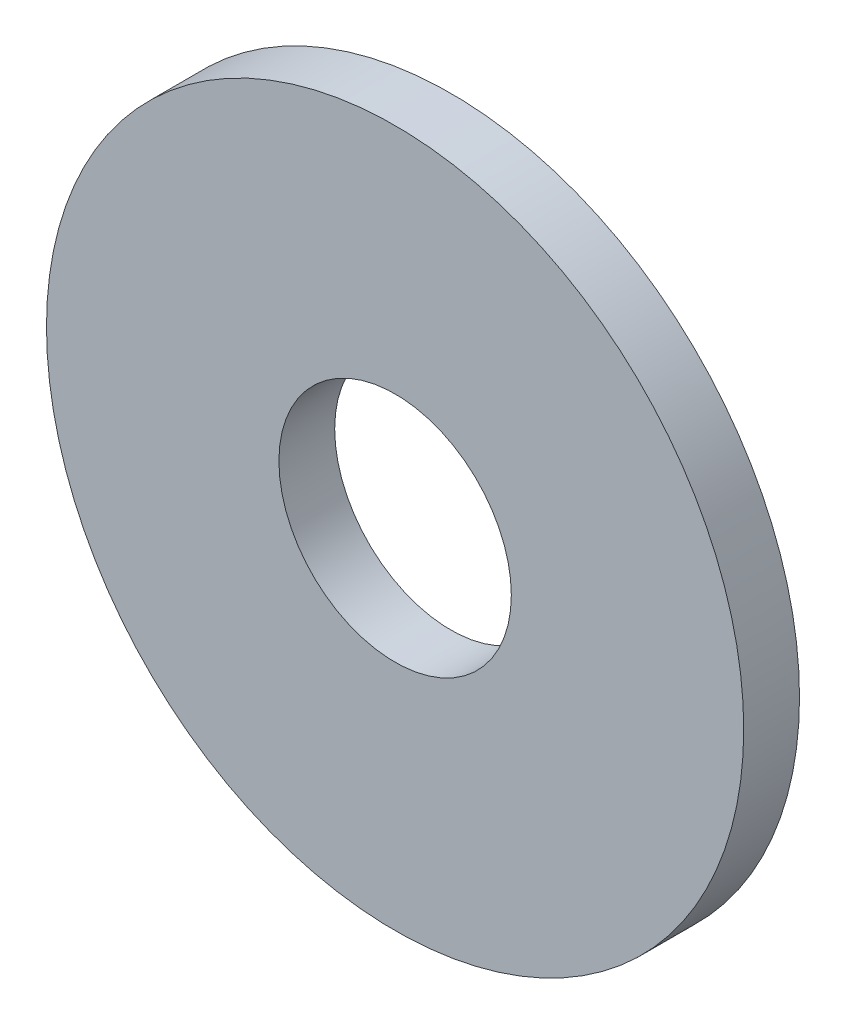
SolidWorks part; units mm, degrees
material "AISI 304"
ref_plane "Front" through (0, 0, 0) normal (0, 0, 1) x (1, 0, 0)
ref_plane "Top" through (0, 0, 0) normal (0, 1, 0) x (1, 0, 0)
ref_plane "Right" through (0, 0, 0) normal (1, 0, 0) x (0, 0, -1)
sketch "Sketch1" plane through (0, 0, 0) normal (0, 0, 1) x (1, 0, 0)
  circle A0 centre (0, 0) radius 2.5
  circle A1 centre (0, 0) radius 7.5
  dimension "D1" = 5
  dimension "D2" = 15
extrude "Boss-Extrude1" add sketch "Sketch1" along normal blind 1.2
